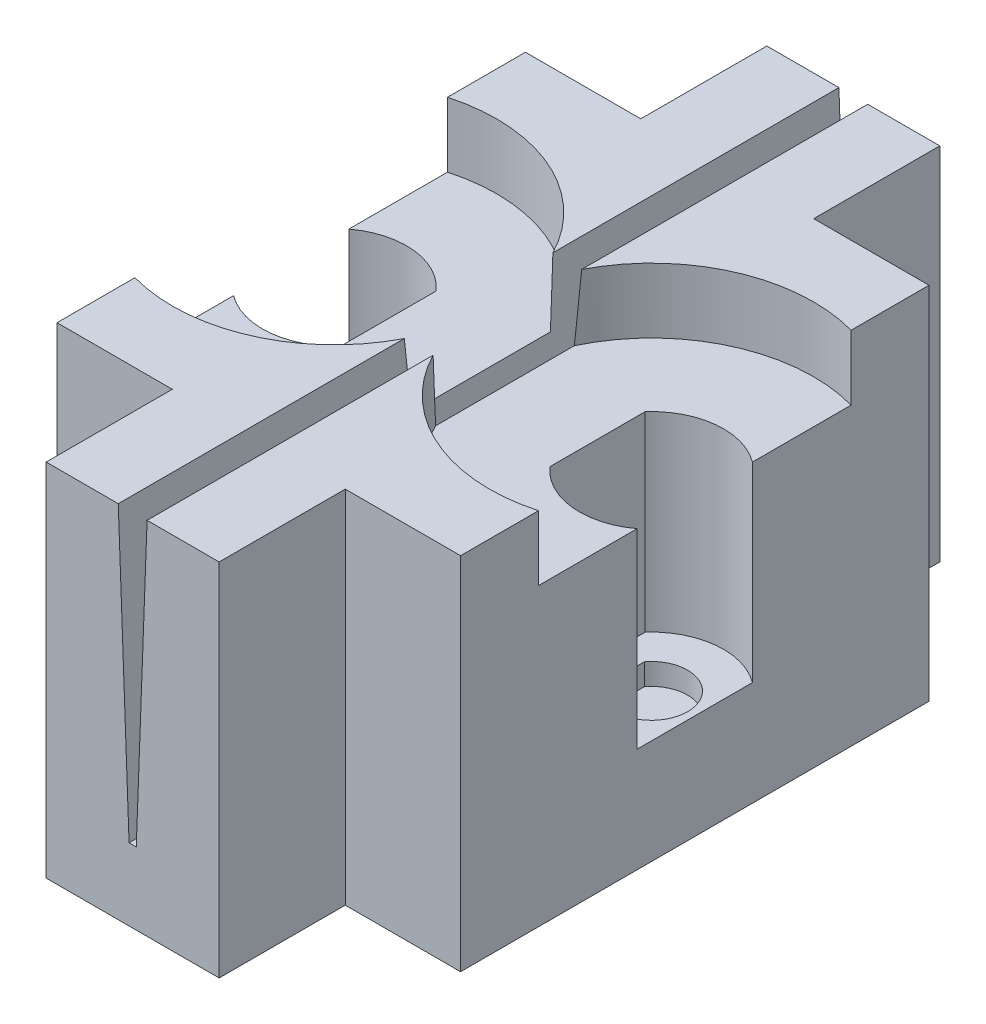
SolidWorks part; units mm, degrees
ref_plane "Front Plane" through (0, 0, 0) normal (0, 0, 1) x (1, 0, 0)
ref_plane "Top Plane" through (0, 0, 0) normal (0, 1, 0) x (1, 0, 0)
ref_plane "Right Plane" through (0, 0, 0) normal (1, 0, 0) x (0, 0, -1)
sketch "Sketch1" plane through (0, 0, 0) normal (0, 1, 0) x (1, 0, 0)
  line L1 (-28, -50) -> (28, -50)
  line L2 (-28, -50) -> (-28, 50)
  line L3 (-28, 50) -> (28, 50)
  line L4 (28, -50) -> (28, 50)
  line L5 (-28, -50) -> (28, 50) construction
  line L6 (-28, 50) -> (28, -50) construction
  point P0 (0, 0)
  dimension "D1" = 100
  dimension "D2" = 56
extrude "Boss-Extrude1" add sketch "Sketch1" along normal blind 50
sketch "Sketch3" plane through (0, 0, 50) normal (0, 0, 1) x (1, 0, 0)
  line L0 (0.5, 50) -> (0.5, 10) construction
  line L1 (-28, 50) -> (28, 50) construction
  line L2 (-28, 0) -> (28, 0) construction
  line L3 (-28, 50) -> (-28, 0) construction
  line L4 (-0.5, 10) -> (-0.5, 50) construction
  line L5 (28, 50) -> (28, 0) construction
  line L11 (-0.5, 10) -> (-2, 50)
  line L13 (2, 50) -> (0.5, 10)
  line L14 (-0.5, 10) -> (0.5, 10)
  line L15 (-2, 50) -> (2, 50)
  point P12 (0, 0)
  dimension "D1" = 10
  dimension "D2" = 28.5
  dimension "D3" = 10
  dimension "D4" = 28.5
  dimension "D5" = 4
extrude "Cut-Extrude2" cut sketch "Sketch3" against normal through all
sketch "Sketch7" plane through (0, 50, 0) normal (0, 1, 0) x (1, 0, 0)
  line L0 (-0.5, 50) -> (-0.5, -50) construction
  line L3 (28, 50) -> (2, 50) construction
  circle A0 centre (22, 0) radius 10
  circle A1 centre (22, 0) radius 21.5 construction
  circle A2 centre (22, 0) radius 22.5
  dimension "D1" = 20
  dimension "D3" = 43
  dimension "D4" = 1
  dimension "D5" = 50
  dimension "D2" = 22.5
extrude "Cut-Extrude4" cut sketch "Sketch7" against normal blind 9
sketch "Sketch9" plane through (0, 50, 0) normal (0, 1, 0) x (1, 0, 0)
  line L0 (14.5, 6.6144) -> (14.5, -6.6144)
  circle A0 centre (22, 0) radius 10 construction
  arc A1 (14.5, 6.6144) -> (14.5, -6.6144) centre (22, 0) cw
  circle A4 centre (22, 0) radius 22.5 construction
  dimension "D1" = 20
  dimension "D2" = 7.5
extrude "Cut-Extrude5" cut sketch "Sketch9" against normal blind 35.5
sketch "Sketch10" plane through (0, 14.5, 0) normal (0, 1, 0) x (1, 0, 0)
  line L0 (18, 3) -> (18, -3)
  arc A1 (18, 3) -> (18, -3) centre (22, 0) cw
  arc A2 (28, 8) -> (14.5, 6.6144) centre (22, 0) ccw construction
  dimension "D1" = 6
  dimension "D2" = 5
  dimension "D3" = 0
  dimension "D4" = 0
extrude "Cut-Extrude6" cut sketch "Sketch10" against normal blind 3
sketch "Sketch11" plane through (0, 50, 0) normal (0, 1, 0) x (1, 0, 0)
  line L0 (14.5, 6.6144) -> (14.5, -6.6144)
  arc A0 (14.5, 6.6144) -> (14.5, -6.6144) centre (22, 0) ccw
extrude "Cut-Extrude7" cut sketch "Sketch11" against normal blind 9
mirror "Mirror1" about plane through (0, 0, 0) normal (1, 0, 0) of "Cut-Extrude7", "Cut-Extrude4", "Cut-Extrude5", "Cut-Extrude6"
sketch "Sketch12" plane through (0, 50, 0) normal (0, 1, 0) x (1, 0, 0)
  line L0 (-2, 50) -> (-2, 10.3078) construction
  line L1 (-28, 50) -> (-12, 50)
  line L2 (-28, 50) -> (-28, 32.5)
  line L3 (-28, 32.5) -> (-12, 32.5)
  line L4 (-12, 50) -> (-12, 32.5)
  line L5 (28, 50) -> (12, 50)
  line L6 (28, 50) -> (28, 32.5)
  line L7 (28, 32.5) -> (12, 32.5)
  line L8 (12, 50) -> (12, 32.5)
  line L9 (-28, -50) -> (-12, -50)
  line L10 (-28, -50) -> (-28, -32.5)
  line L11 (-28, -32.5) -> (-12, -32.5)
  line L12 (-12, -50) -> (-12, -32.5)
  line L13 (28, -50) -> (12, -50)
  line L14 (28, -50) -> (28, -32.5)
  line L15 (28, -32.5) -> (12, -32.5)
  line L16 (12, -50) -> (12, -32.5)
  line L17 (2, 50) -> (2, 10.3078) construction
  line L18 (2, -10.3078) -> (2, -50) construction
  line L19 (-2, -10.3078) -> (-2, -50) construction
  arc A1 (-28, -21.6852) -> (-2, -10.3078) centre (-22, 0) ccw construction
  arc A2 (1.6625, -9.6248) -> (28, -21.6852) centre (22, 0) ccw construction
  arc A3 (28, 21.6852) -> (2, 10.3078) centre (22, 0) ccw construction
  arc A4 (-2, 10.3078) -> (-28, 21.6852) centre (-22, 0) ccw construction
  dimension "D5" = 32.5
  dimension "D1" = 10
  dimension "D2" = 10
  dimension "D3" = 10
  dimension "D4" = 10
  dimension "D6" = 32.5
  dimension "D7" = 32.5
  dimension "D8" = 32.5
extrude "Cut-Extrude8" cut sketch "Sketch12" against normal through all
